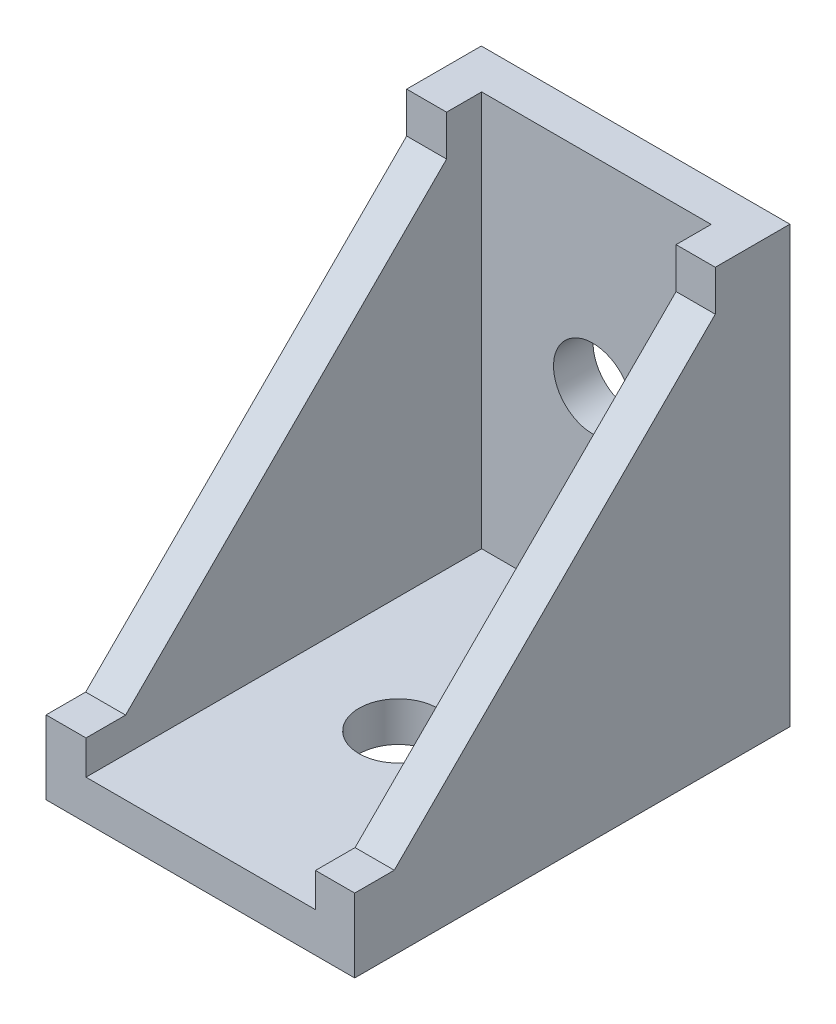
SolidWorks part; units mm, degrees
ref_plane "Front Plane" through (0, 0, 0) normal (0, 0, 1) x (1, 0, 0)
ref_plane "Top Plane" through (0, 0, 0) normal (0, 1, 0) x (1, 0, 0)
ref_plane "Right Plane" through (0, 0, 0) normal (1, 0, 0) x (0, 0, -1)
sketch "Sketch1" plane through (0, 0, 0) normal (0, 0, 1) x (1, 0, 0)
  line L1 (0, 0) -> (19.812, 0)
  line L2 (0, 0) -> (0, -27.94)
  line L3 (0, -27.94) -> (19.812, -27.94)
  line L4 (19.812, 0) -> (19.812, -27.94)
  dimension "D1" = 27.94
  dimension "D2" = 19.812
extrude "Boss-Extrude1" add sketch "Sketch1" along normal blind 27.94
sketch "Sketch2" plane through (0, 0, 27.94) normal (0, 0, 1) x (1, 0, 0)
  line L0 (19.812, 0) -> (0, 0) construction
  line L1 (2.5635, 0) -> (17.2955, 0)
  line L2 (2.5635, 0) -> (2.5635, -25.4)
  line L3 (2.5635, -25.4) -> (17.2955, -25.4)
  line L4 (17.2955, 0) -> (17.2955, -25.4)
  dimension "D1" = 25.4
  dimension "D2" = 14.732
extrude "Cut-Extrude2" cut sketch "Sketch2" against normal blind 25.4 contours L2 L1 L4 L3
sketch "Sketch3" plane through (19.812, 0, 0) normal (1, 0, 0) x (0, 0, -1)
  line L0 (-27.94, -23.2177) -> (-25.4, -23.2177)
  line L1 (-27.94, -27.94) -> (-27.94, 0) construction
  line L2 (-25.4, -23.2177) -> (-4.792, -2.6096)
  line L3 (-4.792, -2.6096) -> (-4.792, 0)
  line L4 (-27.94, 0) -> (0, 0) construction
  line L5 (-27.94, 0) -> (-27.94, -23.2177)
  dimension "D1" = 2.54
extrude "Cut-Extrude3" cut sketch "Sketch3" against normal through all both and the other way through all
hole_wizard "#8 (0.199) Diameter Hole1" positions "Sketch4" profile "Sketch5" hole size "#8" standard "ANSI Inch" end condition through all
sketch "Sketch4" plane through (0, -25.4, 0) normal (0, 1, 0) x (1, 0, 0)
  point P0 (10.0166, -15.3438)
sketch "Sketch5" plane through (10.0166, -25.4, 15.3438) normal (1, 0, 0) x (0, 0, 1)
  line L0 (0, 0) -> (0, 2.54)
  line L1 (0, 2.54) -> (2.5273, 2.54)
  line L2 (2.5273, 2.54) -> (2.5273, 0)
  line L5 (2.5273, 0) -> (0, 0)
  line L11 (0, -6.35) -> (0, 107.95) construction
  dimension "Thru Hole Dia." = 5.0546
  dimension "Thru Hole Depth" = 2.54
hole_wizard "#8 (0.199) Diameter Hole2" positions "Sketch6" profile "Sketch7" hole size "#8" standard "ANSI Inch" end condition through all
sketch "Sketch6" plane through (0, 0, 2.54) normal (0, 0, 1) x (1, 0, 0)
  point P0 (9.7032, -12.9281)
sketch "Sketch7" plane through (9.7032, -12.9281, 2.54) normal (1, 0, 0) x (0, -1, 0)
  line L0 (0, 0) -> (0, 2.54)
  line L1 (0, 2.54) -> (2.5273, 2.54)
  line L2 (2.5273, 2.54) -> (2.5273, 0)
  line L5 (2.5273, 0) -> (0, 0)
  line L11 (0, -6.35) -> (0, 107.95) construction
  dimension "Thru Hole Dia." = 5.0546
  dimension "Thru Hole Depth" = 2.54
